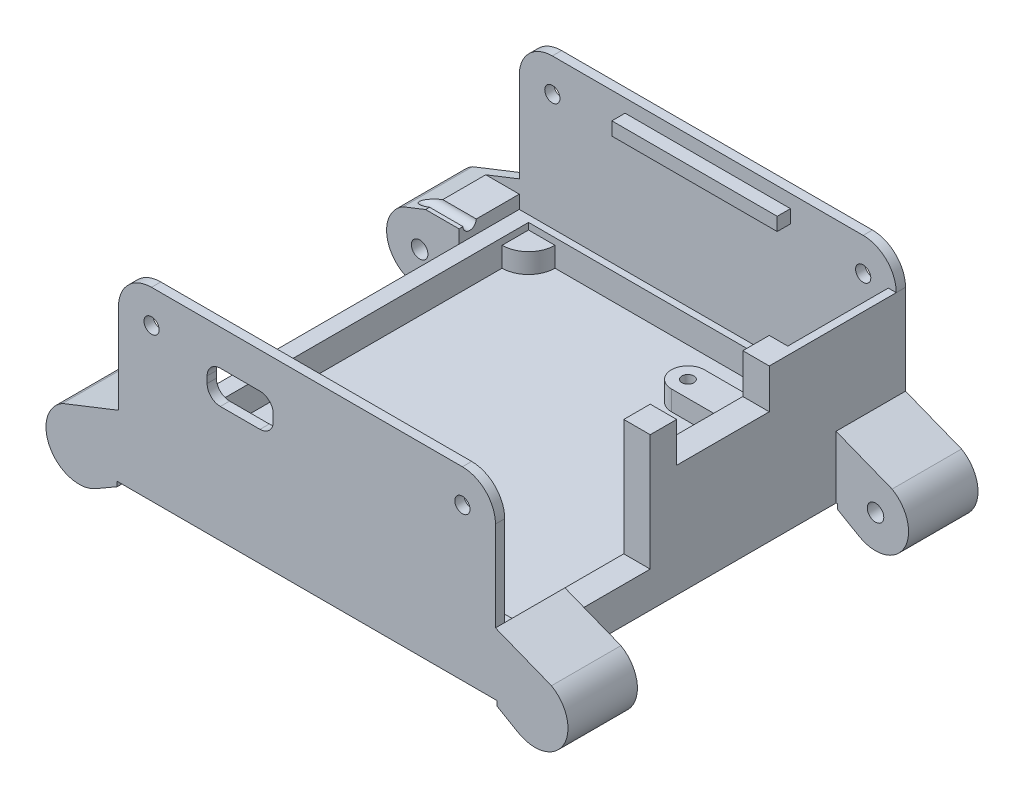
SolidWorks part; units mm, degrees
ref_plane "Front Plane" through (0, 0, 0) normal (0, 0, 1) x (1, 0, 0)
ref_plane "Top Plane" through (0, 0, 0) normal (0, 1, 0) x (1, 0, 0)
ref_plane "Right Plane" through (0, 0, 0) normal (1, 0, 0) x (0, 0, -1)
sketch "Sketch1" plane through (0, 0, 0) normal (0, 1, 0) x (1, 0, 0)
  line L1 (-28.5, 31) -> (28.5, 31)
  line L2 (-28.5, 31) -> (-28.5, -31)
  line L3 (-28.5, -31) -> (28.5, -31)
  line L4 (28.5, 31) -> (28.5, -31)
  line L5 (-28.5, 31) -> (28.5, -31) construction
  line L6 (-28.5, -31) -> (28.5, 31) construction
  point P0 (0, 0)
  dimension "D1" = 62
  dimension "D2" = 57
extrude "Boss-Extrude1" add sketch "Sketch1" along normal blind 6
sketch "Sketch4" plane through (0, 6, 0) normal (0, 1, 0) x (1, 0, 0)
  line L0 (28.5, 31) -> (-28.5, 31) construction
  line L1 (-26.1, 28.6) -> (24.5, 28.6)
  line L2 (-26.1, 28.6) -> (-26.1, -27)
  line L3 (-26.1, -27) -> (24.5, -27)
  line L4 (24.5, 28.6) -> (24.5, -27)
  line L5 (-28.5, 31) -> (-28.5, -31) construction
  dimension "D1" = 2.4
  dimension "D2" = 2.4
  dimension "D3" = 50.6
  dimension "D4" = 55.6
extrude "Cut-Extrude1" cut sketch "Sketch4" against normal blind 4
sketch "Sketch5" plane through (0, 2, 0) normal (0, 1, 0) x (1, 0, 0)
  line L0 (24.5, -27) -> (24.5, 28.6) construction
  line L1 (-26.1, -27) -> (-18.1, -27)
  line L2 (-26.1, -27) -> (-26.1, -21)
  line L3 (-26.1, -21) -> (-20.6, -21)
  line L5 (24.5, 23.6) -> (5.5, 23.6)
  line L6 (24.5, 23.6) -> (24.5, 18.6)
  line L7 (24.5, 18.6) -> (5.5, 18.6)
  line L9 (24.5, 28.6) -> (-26.1, 28.6) construction
  line L10 (-26.1, 24.6) -> (-26.1, 28.6)
  line L11 (24.5, -27) -> (-18.1, -27)
  line L12 (24.5, -27) -> (24.5, -23.5)
  line L13 (24.5, -23.5) -> (-18.1, -23.5)
  line L14 (-26.1, 28.6) -> (-22.1, 28.6)
  arc A0 (5.5, 23.6) -> (5.5, 18.6) centre (5.5, 21.1) ccw
  arc A1 (-18.1, -23.5) -> (-20.6, -21) centre (-20.6, -23.5) ccw
  arc A2 (-26.1, 24.6) -> (-22.1, 28.6) centre (-26.1, 28.6) ccw
  point P16 (-18.1628, -22.0004)
  dimension "D6" = 2.5
  dimension "D1" = 8
  dimension "D2" = 5
  dimension "D3" = 19
  dimension "D4" = 7.5
  dimension "D5" = 5
  dimension "D7" = 4
extrude "Boss-Extrude2" add sketch "Sketch5" along normal blind 3
sketch "Sketch6" plane through (0, 5, 0) normal (0, 1, 0) x (1, 0, 0)
  line L0 (-26.1, -21) -> (-26.1, -27) construction
  line L1 (-26.1, -27) -> (24.5, -27) construction
  circle A0 centre (5.5, 21.1) radius 0.9
  circle A1 centre (-21.1, -24.5) radius 0.9
  dimension "D1" = 1.8
  dimension "D2" = 1.8
  dimension "D3" = 5
  dimension "D4" = 2.5
extrude "Cut-Extrude2" cut sketch "Sketch6" against normal up to surface (3 mm away) up to face at (-0.4685, 2, -6.9899)
sketch "Sketch7" plane through (0, 0, 31) normal (0, 0, 1) x (1, 0, 0)
  line L0 (-28.5, 0) -> (-31.9641, -2)
  line L1 (-28.5, 6) -> (-28.5, 0) construction
  line L2 (-28.5, 0) -> (-28.5, 10)
  line L5 (-31.9641, -2) -> (-36.9641, 6.6603) construction
  line L6 (-36.9641, 6.6603) -> (-28.5, 10)
  line L7 (0, 6) -> (0, 0) construction
  line L8 (-28.5, 6) -> (28.5, 6) construction
  line L9 (31.9641, -2) -> (36.9641, 6.6603) construction
  line L10 (36.9641, 6.6603) -> (28.5, 10)
  line L11 (28.5, 0) -> (28.5, 10)
  line L12 (28.5, 0) -> (31.9641, -2)
  arc A0 (-36.9641, 6.6603) -> (-31.9641, -2) centre (-34.4641, 2.3301) ccw
  arc A1 (36.9641, 6.6603) -> (31.9641, -2) centre (34.4641, 2.3301) cw
  dimension "D1" = 120
  dimension "D2" = 10
  dimension "D3" = 4
  dimension "D4" = 10
extrude "Boss-Extrude3" add sketch "Sketch7" against normal blind 10.5
mirror "Mirror4" about plane through (0, 0, 0) normal (0, 0, 1) of "Boss-Extrude3"
sketch "Sketch8" plane through (0, 0, 20.5) normal (0, 0, -1) x (-1, 0, 0)
  line L0 (0, 6) -> (0, 0) construction
  line L1 (-28.5, 6) -> (28.5, 6) construction
  circle A0 centre (34.4641, 2.3301) radius 1.25
  circle A1 centre (-34.4641, 2.3301) radius 1.25
  dimension "D1" = 2.5
extrude "Cut-Extrude3" cut sketch "Sketch8" against normal offset from surface (7.5 mm away) 3 up to face at (0, 3.6321, 31)
sketch "Sketch9" plane through (0, 0, -20.5) normal (0, 0, 1) x (1, 0, 0)
  line L0 (0, -6.9684) -> (0, 6.9684) construction
  circle A1 centre (-34.4641, 2.3301) radius 1.25
  circle A2 centre (34.4641, 2.3301) radius 1.25
  dimension "D1" = 2.5
extrude "Cut-Extrude4" cut sketch "Sketch9" against normal offset from surface (7.5 mm away) 3 up to face at (0, 3.6321, -31)
sketch "Sketch10" plane through (0, 6, 0) normal (0, 1, 0) x (1, 0, 0)
  line L0 (28.5, 20.5) -> (28.5, 31) construction
  line L1 (-28.5, 31) -> (28.5, 31)
  line L2 (-28.5, 31) -> (-28.5, 29.6)
  line L3 (-28.5, 29.6) -> (28.5, 29.6)
  line L4 (28.5, 31) -> (28.5, 29.6)
  line L5 (28.5, -20.5) -> (28.5, -31) construction
  line L6 (-28.5, -31) -> (28.5, -31)
  line L7 (-28.5, -31) -> (-28.5, -29.6)
  line L8 (-28.5, -29.6) -> (28.5, -29.6)
  line L9 (28.5, -31) -> (28.5, -29.6)
  dimension "D1" = 1.4
  dimension "D2" = 1.4
extrude "Boss-Extrude4" add sketch "Sketch10" along normal blind 22.6
fillet "Fillet2" radius 5 4 edges at (28.5, 28.6, -30.3) (28.5, 28.6, 30.3) (-28.5, 28.6, 30.3) (-28.5, 28.6, -30.3)
sketch "Sketch15" plane through (0, 2, 0) normal (0, 1, 0) x (1, 0, 0)
  line L1 (17.3, 27.5) -> (27.3, 27.5)
  line L2 (17.3, 27.5) -> (17.3, 23.6)
  line L3 (17.3, 23.6) -> (27.3, 23.6)
  line L4 (27.3, 27.5) -> (27.3, 23.6)
  line L5 (28.5, 20.5) -> (28.5, 29.6) construction
  line L6 (24.5, 23.6) -> (5.5, 23.6) construction
  dimension "D1" = 1.2
  dimension "D2" = 10
extrude "Cut-Extrude8" cut sketch "Sketch15" against normal through all both and the other way through all
sketch "Sketch18" plane through (0, 0, 29.6) normal (0, 0, -1) x (-1, 0, 0)
  line L0 (-28.5, 6) -> (28.5, 6) construction
  line L1 (5.1, 23.2) -> (15.1, 23.2)
  line L2 (5.1, 23.2) -> (5.1, 18.2)
  line L3 (5.1, 18.2) -> (15.1, 18.2)
  line L4 (15.1, 23.2) -> (15.1, 18.2)
  line L6 (26.1, 6) -> (26.1, 22.4698) construction
  point P6 (15.1, 20.7)
  dimension "D1" = 12.2
  dimension "D2" = 11
  dimension "D3" = 10
  dimension "D4" = 5
extrude "Cut-Extrude10" cut sketch "Sketch18" against normal through all
fillet "Fillet3" radius 2 4 edges at (-5.1, 18.2, 30.3) (-5.1, 23.2, 30.3) (-15.1, 23.2, 30.3) (-15.1, 18.2, 30.3)
sketch "Sketch20" plane through (-28.5, 0, 0) normal (1, 0, 0) x (0, 0, -1)
  line L2 (29.6, 8) -> (29.6, 10)
  line L3 (29.6, 10) -> (20.5, 10)
  line L4 (20.5, 8) -> (20.5, 10)
  line L5 (29.6, 10) -> (29.6, 6) construction
  line L6 (21.1, 8) -> (20.5, 8)
  line L7 (23.1, 8) -> (29.6, 8)
  line L8 (29.6, 6) -> (20.5, 6) construction
  line L9 (29.6, 23.6) -> (29.6, 10) construction
  arc A0 (21.1, 8) -> (23.1, 8) centre (22.1, 8) ccw
  dimension "D2" = 2
  dimension "D1" = 1
  dimension "D3" = 7.5
extrude "Cut-Extrude12" cut sketch "Sketch20" against normal through all
sketch "Sketch19" plane through (0, 0, 31) normal (0, 0, 1) x (1, 0, 0)
  line L0 (0, -17.1984) -> (0, 17.1984) construction
  circle A0 centre (-23.5, 23.6) radius 1.15
  circle A1 centre (23.5, 23.6) radius 1.15
  dimension "D1" = 2.3
extrude "Cut-Extrude11" cut sketch "Sketch19" against normal through all
sketch "Sketch21" plane through (0, 2, 0) normal (0, 1, 0) x (1, 0, 0)
  line L0 (24.5, 18.6) -> (24.5, 23.6) construction
  line L1 (17.3, 23.6) -> (24.5, 23.6)
  line L2 (17.3, 23.6) -> (17.3, 20.6)
  line L3 (17.3, 20.6) -> (24.5, 20.6)
  line L4 (24.5, 23.6) -> (24.5, 20.6)
  dimension "D1" = 3
extrude "Cut-Extrude13" cut sketch "Sketch21" against normal through all
sketch "Sketch22" plane through (0, 0, 0) normal (0, -1, 0) x (1, 0, 0)
  line L0 (28.5, 20.5) -> (28.5, -20.5) construction
  line L1 (-28.7, 31) -> (28.7, 31)
  line L2 (-28.7, 31) -> (-28.7, -31)
  line L3 (-28.7, -31) -> (28.7, -31)
  line L4 (28.7, 31) -> (28.7, -31)
  dimension "D1" = 57.4
  dimension "D2" = 0.2
extrude "Cut-Extrude14" cut sketch "Sketch22" against normal blind 0.6 and the other way through all
sketch "Sketch23" plane through (0, 6, 0) normal (0, 1, 0) x (1, 0, 0)
  line L0 (24.5, -23.5) -> (24.5, 18.6) construction
  line L1 (24.5, -7.6) -> (28.5, -7.6)
  line L2 (24.5, -7.6) -> (24.5, 14.4)
  line L3 (24.5, 14.4) -> (27.3, 14.4)
  line L6 (28.5, -29.6) -> (-28.5, -29.6) construction
  line L7 (-28.5, 29.6) -> (28.5, 29.6) construction
  line L10 (28.5, 29.6) -> (27.3, 29.6)
  line L11 (27.3, 14.4) -> (27.3, 29.6)
  line L12 (27.3, 23.6) -> (27.3, 27.5) construction
  line L13 (28.5, -7.6) -> (28.5, 29.6)
  line L14 (28.5, -20.5) -> (28.5, 20.5) construction
  dimension "D1" = 22
  dimension "D2" = 22
extrude "Boss-Extrude6" add sketch "Sketch23" along normal up to vertex (17.6 mm away)
sketch "Sketch24" plane through (0, 23.6, 0) normal (0, 1, 0) x (1, 0, 0)
  line L0 (24.5, 14.4) -> (24.5, -7.6) construction
  line L1 (24.5, -3.6) -> (28.5, -3.6)
  line L2 (24.5, -3.6) -> (24.5, 10.4)
  line L3 (24.5, 10.4) -> (28.5, 10.4)
  line L4 (28.5, -3.6) -> (28.5, 10.4)
  line L5 (28.5, -7.6) -> (28.5, 29.6) construction
  line L6 (24.5, -7.6) -> (28.5, -7.6) construction
  dimension "D1" = 14
  dimension "D2" = 4
extrude "Cut-Extrude15" cut sketch "Sketch24" against normal blind 6
sketch "Sketch25" plane through (0, 0, -29.6) normal (0, 0, 1) x (1, 0, 0)
  line L0 (-23.5, 28.6) -> (23.5, 28.6) construction
  line L1 (-12.5, 26.6) -> (12.5, 26.6)
  line L2 (-12.5, 26.6) -> (-12.5, 24.6)
  line L3 (-12.5, 24.6) -> (12.5, 24.6)
  line L4 (12.5, 26.6) -> (12.5, 24.6)
  point P6 (0, 28.6)
  point P7 (0, 26.6)
  dimension "D1" = 25
  dimension "D2" = 2
  dimension "D3" = 2
extrude "Boss-Extrude7" add sketch "Sketch25" along normal blind 2
